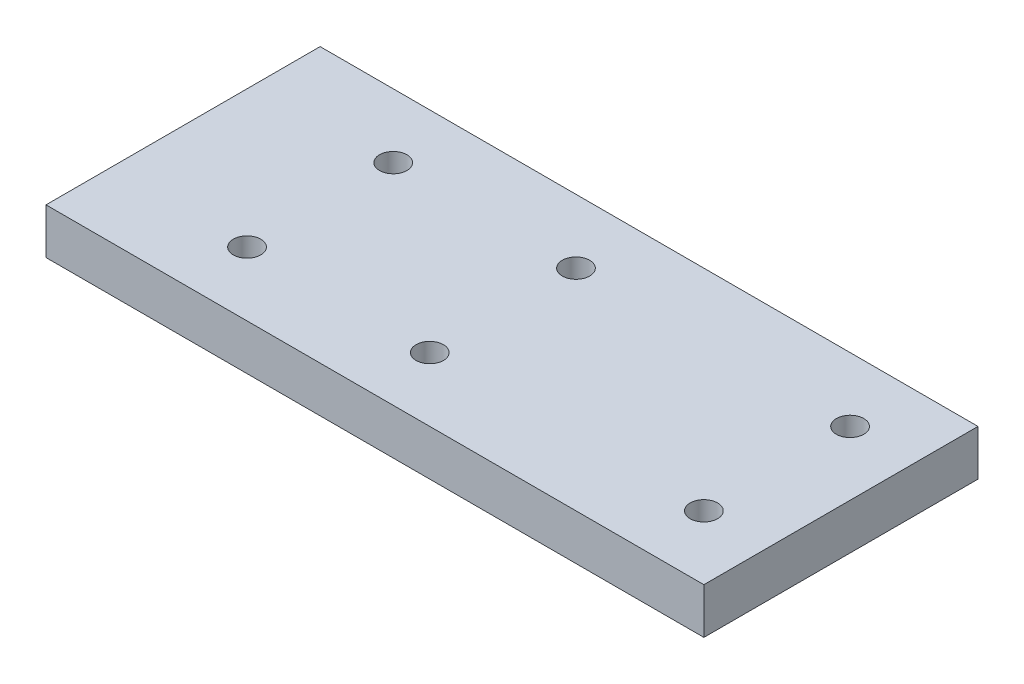
SolidWorks part; units mm, degrees
ref_plane "Front Plane" through (0, 0, 0) normal (0, 0, 1) x (1, 0, 0)
ref_plane "Top Plane" through (0, 0, 0) normal (0, 1, 0) x (1, 0, 0)
ref_plane "Right Plane" through (0, 0, 0) normal (1, 0, 0) x (0, 0, -1)
sketch "Sketch1" plane through (0, 0, 0) normal (0, 1, 0) x (1, 0, 0)
  line L0 (0, 0) -> (8.1209, 0) construction
  line L2 (-15, 15) -> (57, 15)
  line L3 (-15, 15) -> (-15, -15)
  line L4 (-15, -15) -> (57, -15)
  line L5 (57, 15) -> (57, -15)
  circle A1 centre (0, 8) radius 1.5
  circle A2 centre (20, 8) radius 1.5
  circle A3 centre (50, 8) radius 1.5
  circle A4 centre (50, -8) radius 1.5
  circle A5 centre (20, -8) radius 1.5
  circle A6 centre (0, -8) radius 1.5
  point P20 (-15, 0)
  dimension "D1" = 3
  dimension "D5" = 7
  dimension "D2" = 8
  dimension "D3" = 20
  dimension "D4" = 30
  dimension "D6" = 15
  dimension "D7" = 7
extrude "Boss-Extrude1" add sketch "Sketch1" along normal blind 5
sketch "Sketch2" plane through (-15, 0, 0) normal (-1, 0, 0) x (0, 0, 1)
  line L0 (-20, -13.6786) -> (-20, -10.106) construction
  line L1 (-16.2, -3.3786) -> (-16.2, -1.8786)
  line L2 (-16.2, -4.3786) -> (-16.2, -3.3786)
  line L3 (-13, -6.0786) -> (-14.5, -6.0786)
  line L4 (-13, -5.5786) -> (-13, -6.0786)
  line L5 (-10.75, -5.5786) -> (-13, -5.5786)
  line L6 (-16.4675, -13.6786) -> (-23.5325, -13.6786)
  line L7 (-29.8, -9.068) -> (-29.8, -6.1286)
  line L8 (-26.7498, -12.346) -> (-29.6389, -9.4569)
  line L9 (-29.25, -5.5786) -> (-27, -5.5786)
  line L10 (-27, -5.5786) -> (-27, -6.0786)
  line L11 (-27, -6.0786) -> (-25.5, -6.0786)
  line L12 (-23.8, -4.3786) -> (-23.8, -3.3786)
  line L13 (-23.8, -3.3786) -> (-23.8, -1.8786)
  line L14 (-13.2502, -12.346) -> (-10.3611, -9.4569)
  line L15 (-10.2, -9.068) -> (-10.2, -6.1286)
  arc A0 (-13.2502, -12.346) -> (-16.4675, -13.6786) centre (-16.4675, -9.1286) cw
  arc A1 (-14.5, -6.0786) -> (-16.2, -4.3786) centre (-14.5, -4.3786) cw
  arc A2 (-10.2, -9.068) -> (-10.3611, -9.4569) centre (-10.75, -9.068) cw
  arc A3 (-10.75, -5.5786) -> (-10.2, -6.1286) centre (-10.75, -6.1286) cw
  arc A4 (-26.7498, -12.346) -> (-23.5325, -13.6786) centre (-23.5325, -9.1286) ccw
  arc A5 (-29.25, -5.5786) -> (-29.8, -6.1286) centre (-29.25, -6.1286) ccw
  arc A6 (-29.8, -9.068) -> (-29.6389, -9.4569) centre (-29.25, -9.068) ccw
  arc A7 (-25.5, -6.0786) -> (-23.8, -4.3786) centre (-25.5, -4.3786) ccw
  point P34 (0, 0)
  point P36 (0, 0)
  dimension "D1" = 1.5
  dimension "D2" = 20
